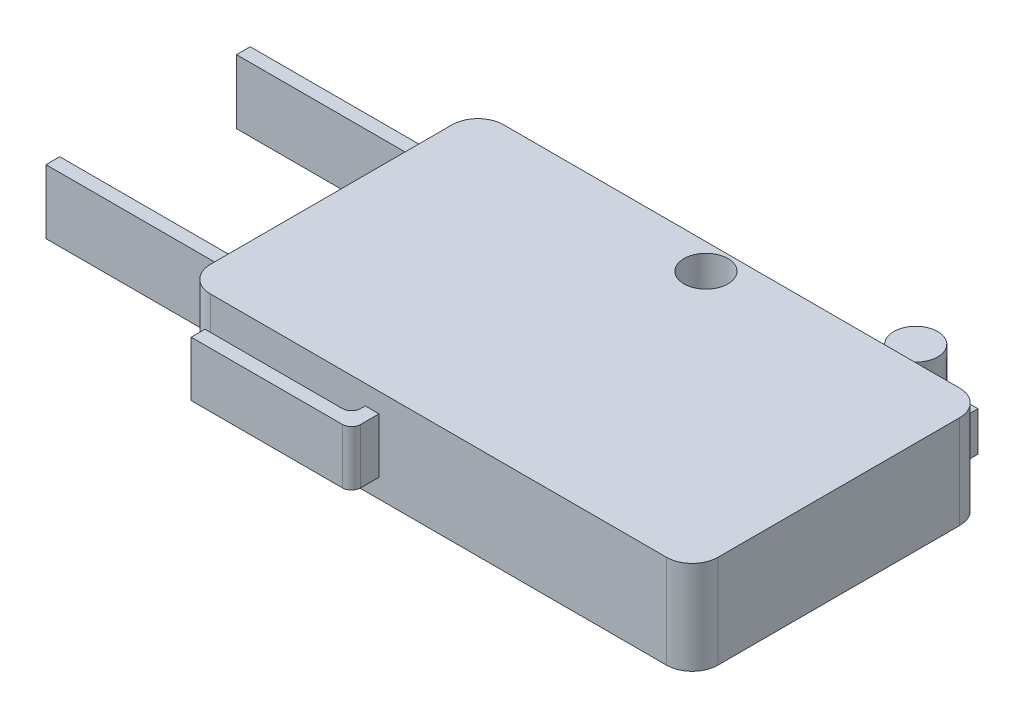
SolidWorks part; units mm, degrees
ref_plane "Front Plane" through (0, 0, 0) normal (0, 0, 1) x (1, 0, 0)
ref_plane "Top Plane" through (0, 0, 0) normal (0, 1, 0) x (1, 0, 0)
ref_plane "Right Plane" through (0, 0, 0) normal (1, 0, 0) x (0, 0, -1)
sketch "Sketch1" plane through (0, 0, 0) normal (0, 1, 0) x (1, 0, 0)
  line L1 (-24.9, 16) -> (24.9, 16)
  line L2 (-27.7, 13.2) -> (-27.7, -13.2)
  line L3 (-24.9, -16) -> (24.9, -16)
  line L4 (27.7, 13.2) -> (27.7, -13.2)
  line L5 (-27.7, 16) -> (27.7, -16) construction
  line L6 (-27.7, -16) -> (27.7, 16) construction
  arc A0 (-24.9, 16) -> (-27.7, 13.2) centre (-24.9, 13.2) ccw
  arc A1 (24.9, 16) -> (27.7, 13.2) centre (24.9, 13.2) cw
  arc A2 (24.9, -16) -> (27.7, -13.2) centre (24.9, -13.2) ccw
  arc A3 (-24.9, -16) -> (-27.7, -13.2) centre (-24.9, -13.2) cw
  point P0 (0, 0)
  dimension "D1" = 2.8
  dimension "D2" = 2.8
  dimension "D3" = 2.8
  dimension "D4" = 2.8
extrude "Boss-Extrude2" add sketch "Sketch1" along normal blind 10.2
sketch "Sketch3" plane through (0, 0, -16) normal (0, 0, -1) x (-1, 0, 0)
  line L0 (-24.9, 5.1) -> (-5.3, 5.1) construction
  line L1 (-24.9, 10.2) -> (-24.9, 0) construction
  line L3 (-24.9, 7.25) -> (-5.3, 7.25)
  line L4 (-24.9, 7.25) -> (-24.9, 2.95)
  line L5 (-24.9, 2.95) -> (-5.3, 2.95)
  line L6 (-5.3, 7.25) -> (-5.3, 2.95)
  line L7 (-24.9, 7.25) -> (-5.3, 2.95) construction
  line L8 (-24.9, 2.95) -> (-5.3, 7.25) construction
  point P4 (-15.1, 5.1)
extrude "Boss-Extrude3" add sketch "Sketch3" along normal blind 2
fillet "Fillet3" radius 1 1 edges at (5.3, 5.1, -18)
sketch "Sketch4" plane through (-27.7, 0, 0) normal (-1, 0, 0) x (0, 0, 1)
  line L0 (0, 10.2) -> (0, 0) construction
  line L1 (-13.2, 10.2) -> (13.2, 10.2) construction
  line L2 (0, 5.1) -> (10.4, 5.1) construction
  line L3 (0, 5.1) -> (-10.4, 5.1) construction
  line L5 (-11.15, 8.6) -> (-9.65, 8.6)
  line L6 (-11.15, 8.6) -> (-11.15, 1.6)
  line L7 (-11.15, 1.6) -> (-9.65, 1.6)
  line L8 (-9.65, 8.6) -> (-9.65, 1.6)
  line L9 (-11.15, 8.6) -> (-9.65, 1.6) construction
  line L10 (-11.15, 1.6) -> (-9.65, 8.6) construction
extrude "Boss-Extrude4" add sketch "Sketch4" along normal blind 20
sketch "Sketch5" plane through (-27.7, 0, 0) normal (-1, 0, 0) x (0, 0, 1)
  line L0 (0, 0) -> (0, 10.2) construction
  line L1 (-13.2, 10.2) -> (13.2, 10.2) construction
  line L2 (0, 5.1) -> (10.4, 5.1) construction
  line L4 (9.65, 8.6) -> (11.15, 8.6)
  line L5 (9.65, 8.6) -> (9.65, 1.6)
  line L6 (9.65, 1.6) -> (11.15, 1.6)
  line L7 (11.15, 8.6) -> (11.15, 1.6)
  line L8 (9.65, 8.6) -> (11.15, 1.6) construction
  line L9 (9.65, 1.6) -> (11.15, 8.6) construction
extrude "Boss-Extrude5" add sketch "Sketch5" along normal blind 20
sketch "Sketch6" plane through (0, 0, 16) normal (0, 0, 1) x (1, 0, 0)
  line L1 (-7.997, 8.0668) -> (-6.497, 8.0668)
  line L2 (-7.997, 8.0668) -> (-7.997, 2.0668)
  line L3 (-7.997, 2.0668) -> (-6.497, 2.0668)
  line L4 (-6.497, 8.0668) -> (-6.497, 2.0668)
  line L5 (-7.997, 8.0668) -> (-6.497, 2.0668) construction
  line L6 (-7.997, 2.0668) -> (-6.497, 8.0668) construction
  point P0 (-7.247, 5.0668)
extrude "Boss-Extrude7" add sketch "Sketch6" along normal blind 3
sketch "Sketch8" plane through (-7.997, 0, 0) normal (-1, 0, 0) x (0, 0, 1)
  line L1 (17.5, 2.0668) -> (19, 2.0668)
  line L2 (17.5, 2.0668) -> (17.5, 8.0668)
  line L3 (17.5, 8.0668) -> (19, 8.0668)
  line L4 (19, 2.0668) -> (19, 8.0668)
  line L5 (17.5, 2.0668) -> (19, 8.0668) construction
  line L6 (17.5, 8.0668) -> (19, 2.0668) construction
  point P0 (18.25, 5.0668)
extrude "Boss-Extrude8" add sketch "Sketch8" along normal blind 16
fillet "Fillet4" radius 1 1 edges at (-7.997, 5.0668, 17.5)
fillet "Fillet5" radius 1 1 edges at (-6.497, 5.0668, 19)
sketch "Sketch11" plane through (0, 2.95, 0) normal (0, -1, 0) x (1, 0, 0)
  line L0 (24.9, -16) -> (15.1, -16) construction
  line L1 (24.9, -16) -> (-24.9, -16) construction
  line L2 (15.1, -16) -> (15.1, -21) construction
  line L3 (16.6145, -19.1382) -> (16.6145, -16)
  line L4 (13.5855, -19.1382) -> (13.5855, -16)
  line L5 (13.5855, -16) -> (16.6145, -16)
  arc A0 (13.5855, -19.1382) -> (16.6145, -19.1382) centre (15.1, -21) ccw
extrude "Boss-Extrude10" add sketch "Sketch11" against normal blind 4
sketch "Sketch12" plane through (0, 10.2, 0) normal (0, 1, 0) x (1, 0, 0)
  line L0 (0, 16) -> (0, 13.2) construction
  line L1 (24.9, 16) -> (-24.9, 16) construction
  circle A0 centre (0, 13.2) radius 2.4
extrude "Cut-Extrude1" cut sketch "Sketch12" against normal blind 19
